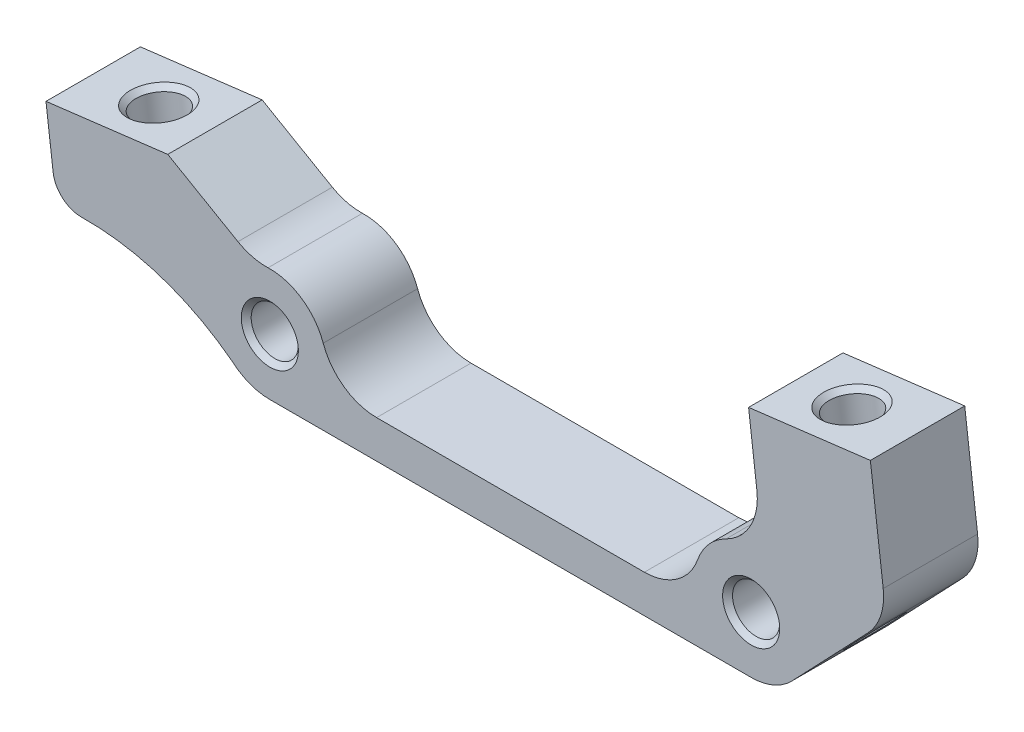
SolidWorks part; units mm, degrees
material "1060 Сплав"
ref_plane "Спереди" through (0, 0, 0) normal (0, 0, 1) x (1, 0, 0)
ref_plane "Сверху" through (0, 0, 0) normal (0, 1, 0) x (1, 0, 0)
ref_plane "Справа" through (0, 0, 0) normal (1, 0, 0) x (0, 0, -1)
sketch "Эскиз1" plane through (0, 0, 0) normal (0, 0, 1) x (1, 0, 0)
  line L0 (-82.7455, -26.8978) -> (159.9328, -26.8978) construction
  line L1 (-82.7455, -26.8978) -> (164.1479, 3.4169) construction
  line L2 (159.9328, -20.8978) -> (-82.7455, -20.8978) construction
  line L3 (118.2545, -20.8978) -> (112.7185, 24.1897) construction
  line L4 (130.8832, -0.6675) -> (132.2434, -11.745)
  line L5 (130.8832, -0.6675) -> (117.9801, -2.2518)
  line L6 (78.5682, -22.8978) -> (106.9408, -22.8978)
  line L7 (67.2545, -26.8978) -> (118.2545, -26.8978)
  line L8 (117.9801, -2.2518) -> (118.8608, -9.4247)
  line L9 (122.596, -25.0393) -> (130.6296, -16.6177)
  line L10 (43.5392, -11.392) -> (56.4423, -9.8077)
  line L11 (43.5392, -11.392) -> (44.2896, -17.5042)
  line L12 (56.4423, -9.8077) -> (63.8766, -14.0999)
  circle A0 centre (67.2545, -20.8978) radius 2.5
  circle A1 centre (118.2545, -20.8978) radius 2.5
  arc A2 (118.2545, -26.8978) -> (122.596, -25.0393) centre (118.2545, -20.8978) ccw
  arc A3 (72.9114, -18.8978) -> (67.0656, -14.9008) centre (67.2545, -20.8978) ccw
  arc A4 (106.9408, -22.8978) -> (112.5977, -18.8978) centre (106.9408, -16.8978) ccw
  arc A5 (78.5682, -22.8978) -> (72.9114, -18.8978) centre (78.5682, -16.8978) cw
  arc A6 (115.58, -15.5269) -> (112.5977, -18.8978) centre (118.2545, -20.8978) ccw
  arc A7 (118.8608, -9.4247) -> (115.58, -15.5269) centre (112.9056, -10.1559) cw
  arc A8 (132.2434, -11.745) -> (130.6296, -16.6177) centre (126.2881, -12.4762) cw
  arc A9 (47.318, -20.1381) -> (63.2926, -25.4037) centre (47.7505, -45.6905) cw
  arc A10 (63.2926, -25.4037) -> (67.2545, -26.8978) centre (67.2545, -20.8978) ccw
  arc A11 (63.8766, -14.0999) -> (67.0656, -14.9008) centre (66.8766, -8.9038) ccw
  arc A12 (44.2896, -17.5042) -> (47.318, -20.1381) centre (47.2673, -17.1386) ccw
  point P25 (119.5502, -15.0394)
  point P28 (132.5894, -14.5632)
  point P39 (44.636, -20.325)
  dimension "D3" = 5
  dimension "D4" = 5
  dimension "D5" = 51
  dimension "D6" = 150
  dimension "D11" = 6
  dimension "D12" = 6
  dimension "D13" = 6
  dimension "D18" = 6
  dimension "D19" = 3
  dimension "D1" = 7
  dimension "D2" = 6
  dimension "D7" = 15
  dimension "D8" = 14
  dimension "D9" = 13
  dimension "D10" = 4
  dimension "D14" = 13
  dimension "D15" = 88
  dimension "D16" = 9
  dimension "D17" = 30
extrude "Бобышка-Вытянуть1" add sketch "Эскиз1" along normal blind 10
cosmetic thread "Отверстие резьбы1"
cosmetic thread "Отверстие резьбы2"
hole_wizard "Отверстие обработанное метчиком M61" positions "Эскиз3" profile "Эскиз2" tap size "M6" standard "DIN" end condition through all
sketch "Эскиз3" plane through (0, 0, 10) normal (0, 0, 1) x (1, 0, 0)
  point P0 (67.2545, -20.8978)
  point P1 (118.2545, -20.8978)
sketch "Эскиз2" plane through (67.2545, -20.8978, 10) normal (1, 0, 0) x (0, -1, 0)
  line L0 (0, 0) -> (0, 10)
  line L1 (0, 10) -> (3.025, 10)
  line L2 (2.5, 9.475) -> (2.5, 0.525)
  line L3 (2.5, 0.525) -> (3.025, 0)
  line L5 (3.025, 0) -> (0, 0)
  line L6 (-2.5, 0.525) -> (-3.025, 0) construction
  line L7 (3.025, 10) -> (2.5, 9.475)
  line L8 (-3.025, 10) -> (-2.5, 9.475) construction
  line L11 (0, -6.35) -> (0, 107.95) construction
  dimension "Диаметр проходного сверла" = 5
  dimension "Глубина проходного сверла" = 10
  dimension "Диаметр передней зенковки" = 6.05
  dimension "Угол передней зенковки" = 90
  dimension "Диаметр задней зенковки" = 6.05
  dimension "Угол задней зенковки" = 90
hole_wizard "Отверстие обработанное метчиком M62" positions "Эскиз5" profile "Эскиз4" tap size "M6" standard "DIN" end condition through all
sketch "Эскиз5" plane through (2.0246, -16.4894, 0) normal (-0.1219, 0.9925, 0) x (-0.9925, -0.1219, 0)
  line L0 (-129.8263, 5) -> (-23.6631, 5) construction
  line L1 (-129.8263, 10) -> (-129.8263, 0) construction
  line L2 (-54.8263, 10) -> (-41.8263, 10) construction
  point P0 (-48.8263, 5)
  point P1 (-122.8263, 5)
  dimension "D1" = 74
  dimension "D2" = 7
  dimension "D3" = 5
cosmetic thread "Отверстие резьбы3"
cosmetic thread "Отверстие резьбы4"
sketch "Эскиз4" plane through (50.487, -10.539, 5) normal (0, 0, 1) x (-0.9925, -0.1219, 0)
  line L0 (0, 0) -> (0, 26.206)
  line L1 (0, 26.206) -> (2.5, 26.206)
  line L2 (2.5, 26.206) -> (2.5, 0.525)
  line L3 (2.5, 0.525) -> (3.025, 0)
  line L5 (3.025, 0) -> (0, 0)
  line L6 (-2.5, 0.525) -> (-3.025, 0) construction
  line L11 (0, -6.35) -> (0, 107.95) construction
  dimension "Диаметр проходного сверла" = 5
  dimension "Глубина проходного сверла" = 26.206
  dimension "Диаметр передней зенковки" = 6.05
  dimension "Угол передней зенковки" = 90
sketch "Sketch1" plane through (0, 0, 10) normal (0, 0, 1) x (1, 0, 0)
  line L0 (67.2545, -20.8978) -> (118.2545, -20.8978)
